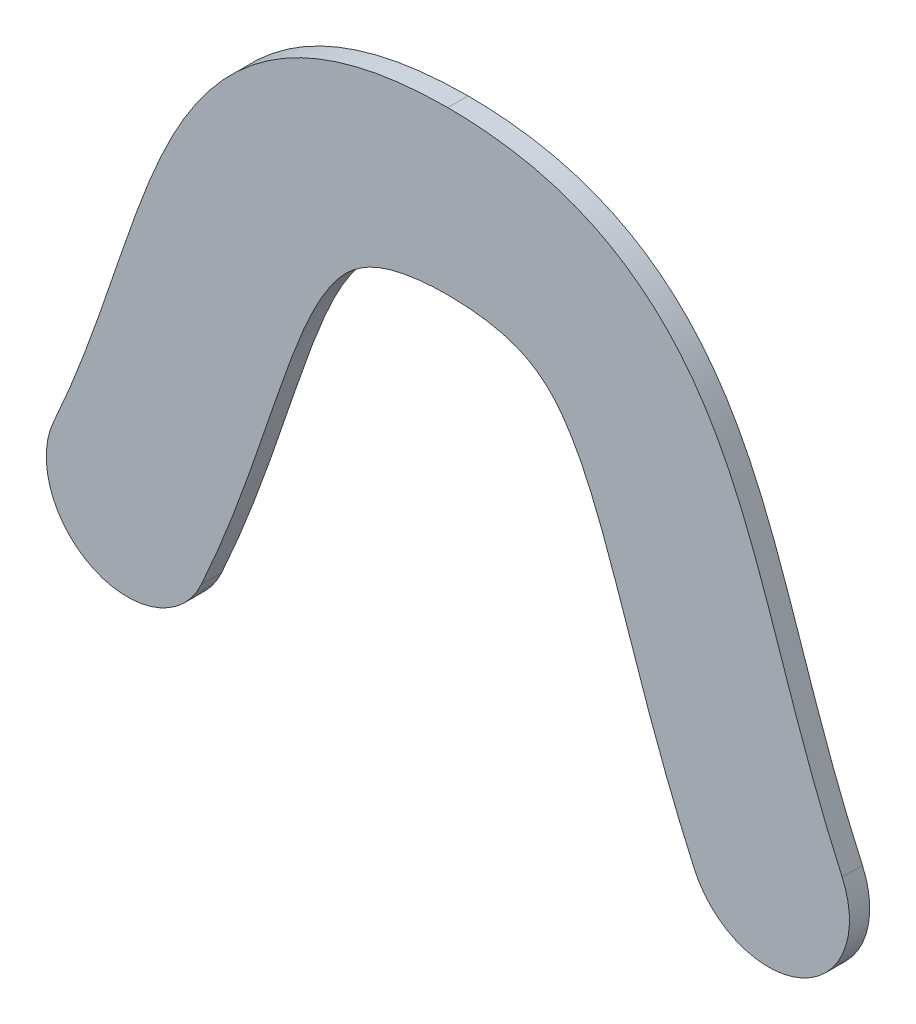
SolidWorks part; units mm, degrees
ref_plane "Front Plane" through (0, 0, 0) normal (0, 0, 1) x (1, 0, 0)
ref_plane "Top Plane" through (0, 0, 0) normal (0, 1, 0) x (1, 0, 0)
ref_plane "Right Plane" through (0, 0, 0) normal (1, 0, 0) x (0, 0, -1)
sketch "Esboço1" plane through (0, 0, 0) normal (0, 0, 1) x (1, 0, 0)
  line L1 (0, -20) -> (0, 28.8095) construction
  arc A0 (38.8937, -9.4827) -> (24.3318, -16.1123) centre (31.6128, -12.7975) cw
  arc A1 (-38.8937, -9.4827) -> (-24.3318, -16.1123) centre (-31.6128, -12.7975) ccw
  spline S0 degree 1 poles (0, 36.8096) (38.8937, -9.4827) knots 0 0 1 1 construction
  spline S1 degree 1 poles (0, 36.8096) (-38.8937, -9.4827) knots 0 0 1 1 construction
  spline S2 degree 3 poles (0, 28.8095) (-22.5521, 28.7004) (-21.0921, 10.3111) (-31.6128, -12.7975) knots 0 0 0 0 1 1 1 1 construction
  spline S3 degree 3 poles (0, 28.8095) (22.5521, 28.7004) (21.0921, 10.3111) (31.6128, -12.7975) knots 0 0 0 0 1 1 1 1 construction
  spline S4 degree 3 poles (38.8937, -9.4827) (38.5917, -8.8193) (37.9988, -7.4779) (36.8945, -4.8369) (35.6304, -1.5703) (34.256, 2.2736) (32.5416, 7.2947) (30.4853, 13.3624) (27.6446, 20.2987) (24.3466, 25.7791) (20.7054, 29.7244) (17.4256, 32.3035) (13.6376, 34.3527) (9.4441, 35.7887) (5.6674, 36.4809) (2.4904, 36.7574) (0.824, 36.8056) (0, 36.8096) knots -0.000572 -0.000572 -0.000572 -0.000572 0.030696 0.061964 0.124499 0.187035 0.249571 0.374642 0.499714 0.624785 0.687321 0.749857 0.812393 0.874928 0.937464 0.968732 1 1 1 1
  spline S5 degree 3 poles (0, 36.8096) (-0.824, 36.8056) (-2.4904, 36.7574) (-5.6674, 36.4809) (-9.4441, 35.7887) (-13.6376, 34.3527) (-17.4256, 32.3035) (-20.7054, 29.7244) (-24.3466, 25.7791) (-27.6446, 20.2987) (-30.4853, 13.3624) (-32.5416, 7.2947) (-34.256, 2.2736) (-35.6304, -1.5703) (-36.8945, -4.8369) (-37.9988, -7.4779) (-38.5917, -8.8193) (-38.8937, -9.4827) knots -0.000572 -0.000572 -0.000572 -0.000572 0.030696 0.061964 0.124499 0.187035 0.249571 0.312107 0.374642 0.499714 0.624785 0.749857 0.812393 0.874928 0.937464 0.968732 1 1 1 1
  spline S6 degree 1 poles (0, 20.8094) (24.3318, -16.1123) knots 0 0 1 1 construction
  spline S7 degree 1 poles (0, 20.8094) (-24.3318, -16.1123) knots 0 0 1 1 construction
  spline S8 degree 3 poles (24.3318, -16.1123) (23.9838, -15.3478) (23.2978, -13.7957) (22.0407, -10.789) (20.6288, -7.1387) (19.1464, -2.9914) (17.3775, 2.1921) (15.4286, 7.9298) (13.1813, 13.3248) (10.9057, 16.9244) (9.0768, 18.5955) (7.2629, 19.5961) (5.7917, 20.1167) (4.3265, 20.4474) (3.0693, 20.6415) (1.8756, 20.749) (0.8385, 20.7971) (0.2759, 20.8077) (0, 20.8094) knots 0.00071 0.00071 0.00071 0.00071 0.031938 0.063165 0.125621 0.188077 0.250532 0.375444 0.500355 0.625266 0.750177 0.812633 0.875089 0.906317 0.937544 0.968772 0.984386 1 1 1 1
  spline S9 degree 3 poles (0, 20.8094) (-0.2759, 20.8077) (-0.8385, 20.7971) (-1.8756, 20.749) (-3.0693, 20.6415) (-4.3265, 20.4474) (-5.7917, 20.1167) (-7.2629, 19.5961) (-9.0768, 18.5955) (-10.9057, 16.9244) (-13.1813, 13.3248) (-15.4286, 7.9298) (-17.3775, 2.1921) (-19.1464, -2.9914) (-20.6288, -7.1387) (-22.0407, -10.789) (-23.2978, -13.7957) (-23.9838, -15.3478) (-24.3318, -16.1123) knots 0.00071 0.00071 0.00071 0.00071 0.016324 0.031938 0.063165 0.094393 0.125621 0.188077 0.250532 0.375444 0.500355 0.625266 0.750177 0.812633 0.875089 0.937544 0.968772 1 1 1 1
  point P0 (0, -20)
  point P9 (0, 0)
  point P11 (0, -20)
  dimension "D1" = 8
  dimension "D2" = 8
extrude "Ressalto-extrusão1" add sketch "Esboço1" along normal blind 2
